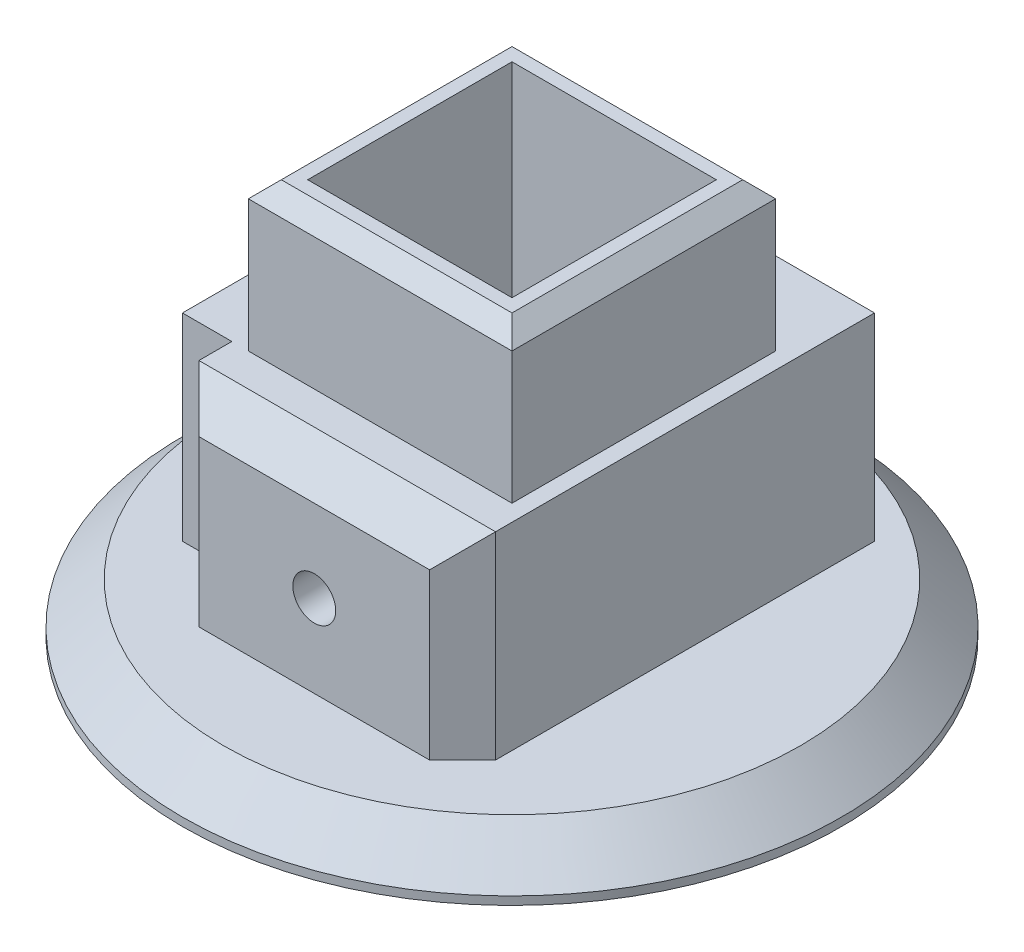
SolidWorks part; units mm, degrees
ref_plane "Front Plane" through (0, 0, 0) normal (0, 0, 1) x (1, 0, 0)
ref_plane "Top Plane" through (0, 0, 0) normal (0, 1, 0) x (1, 0, 0)
ref_plane "Right Plane" through (0, 0, 0) normal (1, 0, 0) x (0, 0, -1)
sketch "Sketch1" plane through (0, 0, 0) normal (0, 1, 0) x (1, 0, 0)
  line L0 (0, 16) -> (0, 0) construction
  line L1 (-8, 16) -> (8, 16)
  line L2 (-8, 16) -> (-8, 0)
  line L10 (8, 16) -> (8, 0)
  line L11 (-8, 0) -> (8, 0)
  dimension "D1" = 16
  dimension "D2" = 16
extrude "Boss-Extrude1" add sketch "Sketch1" along normal blind 24
sketch "Sketch12" plane through (0, 24, 0) normal (0, 1, 0) x (1, 0, 0)
  line L1 (-6.2, 14.2) -> (6.2, 14.2)
  line L2 (-6.2, 14.2) -> (-6.2, 1.8)
  line L3 (-6.2, 1.8) -> (6.2, 1.8)
  line L4 (6.2, 14.2) -> (6.2, 1.8)
  line L5 (0, 0) -> (0, 16) construction
  line L6 (8, 8) -> (-13.65, 8) construction
  line L7 (8, 16) -> (8, 0) construction
  dimension "D1" = 12.4
  dimension "D2" = 12.4
extrude "Cut-Extrude6" cut sketch "Sketch12" against normal offset from surface (22 mm away) 2 up to face at (0, 0, -8)
sketch "Sketch13" plane through (0, 0, 0) normal (0, 1, 0) x (1, 0, 0)
  line L0 (0, 16) -> (0, 0) construction
  circle A0 centre (0, 8) radius 20
  dimension "D1" = 40
extrude "Boss-Extrude2" add sketch "Sketch13" along normal blind 3
chamfer "Chamfer1" distance 2.5 angle 45 1 edges at (0, 3, 12)
sketch "Sketch14" plane through (0, 3, 0) normal (0, 1, 0) x (1, 0, 0)
  line L1 (-8, 16) -> (8, 16)
  line L3 (-8, 23) -> (8, 23)
  line L5 (-8, 0) -> (8, 0)
  line L7 (-8, -4) -> (8, -4)
  line L9 (0, 0) -> (0, 24.5816) construction
  line L10 (-8, 23) -> (-9, 23)
  line L11 (-8, 16) -> (-8, 0)
  line L12 (-8, -4) -> (-9, -4)
  line L13 (-9, 23) -> (-9, -4)
  line L14 (8, -4) -> (9, -4)
  line L15 (8, 23) -> (9, 23)
  line L16 (9, 23) -> (9, -4)
  line L17 (8, 16) -> (8, 0) construction
  line L18 (8, 16) -> (8, 0)
  dimension "D1" = 7
  dimension "D2" = 4
  dimension "D3" = 1
extrude "Boss-Extrude3" add sketch "Sketch14" along normal blind 12
sketch "Sketch5" plane through (0, 0, -23) normal (0, 0, -1) x (-1, 0, 0)
  line L0 (0, 24) -> (0, 0) construction
  line L3 (-22.5, 8) -> (22.5, 8) construction
  line L4 (-2.1, 11.1) -> (2.1, 11.1)
  line L5 (-3.1, 10.1) -> (-3.1, 8.8)
  line L6 (-3.1, 4.9) -> (3.1, 4.9)
  line L7 (3.1, 10.1) -> (3.1, 8.8)
  line L10 (-2.1, 11.1) -> (-3.1, 10.1)
  line L11 (2.1, 11.1) -> (3.1, 10.1)
  line L12 (-3.1, 7.2) -> (-3.1, 4.9)
  line L13 (3.1, 7.2) -> (3.1, 4.9)
  line L14 (-8, 24) -> (8, 24) construction
  arc A0 (-3.1, 8.8) -> (-3.1, 7.2) centre (-3.1, 8) ccw
  arc A1 (3.1, 8.8) -> (3.1, 7.2) centre (3.1, 8) cw
  point P6 (-3.1, 11.1)
  dimension "D4" = 0.8
  dimension "D1" = 8
  dimension "D2" = 6.2
  dimension "D3" = 6.2
extrude "Cut-Extrude1" cut sketch "Sketch5" against normal blind 7.5
sketch "Sketch11" plane through (0, 11.1, 0) normal (0, -1, 0) x (1, 0, 0)
  line L0 (2.1, -15.5) -> (2.1, -23) construction
  line L1 (-2.1, -15.5) -> (2.1, -15.5)
  line L2 (-2.1, -15.5) -> (-2.1, -21)
  line L3 (-2.1, -21) -> (2.1, -21)
  line L4 (2.1, -15.5) -> (2.1, -21)
  line L6 (22.5, -23) -> (-22.5, -23) construction
  dimension "D1" = 2
extrude "Cut-Extrude5" cut sketch "Sketch11" against normal blind 0.1 and the other way blind 6.3
chamfer "Chamfer2" distance 2 angle 45 3 edges at (-9, 9, -23) (9, 9, -23) (0, 15, -23)
chamfer "Chamfer4" distance 2 angle 45 3 edges at (0, 15, 4) (9, 9, 4) (-9, 9, 4)
sketch "Sketch15" plane through (0, 0, -15.5) normal (0, 0, -1) x (-1, 0, 0)
  line L0 (-22.5, 8) -> (22.5, 8) construction
  circle A0 centre (0, 8) radius 1.3
  dimension "D1" = 2.6
extrude "Cut-Extrude7" cut sketch "Sketch15" against normal through all
chamfer "Chamfer5" distance 1 angle 45 4 edges at (0, 24, 0) (-8, 24, -8) (0, 24, -16) (8, 24, -8)
sketch "Esquisse3" plane through (-9, 0, 0) normal (-1, 0, 0) x (0, 0, 1)
  line L0 (9.5, 3) -> (-25.5, 3) construction
  line L1 (0, 3) -> (-15.9265, 3)
  line L2 (0, 3) -> (0, 15)
  line L3 (0, 15) -> (-15.9265, 15)
  line L4 (-15.9265, 3) -> (-15.9265, 15)
  line L5 (-21, 15) -> (2, 15) construction
extrude "Boss.-Extru.1" add sketch "Esquisse3" along normal blind 5
sketch "Esquisse4" plane through (-14, 0, 0) normal (-1, 0, 0) x (0, 0, 1)
  line L0 (-7.965, 24.7266) -> (-7.965, 0.7266) construction
  line L1 (-30.6321, 8) -> (14.3679, 8) construction
  line L2 (-10.065, 11.1) -> (-5.865, 11.1)
  line L3 (-11.065, 10.1) -> (-11.065, 8.8)
  line L4 (-11.065, 4.9) -> (-4.865, 4.9)
  line L5 (-4.865, 10.1) -> (-4.865, 8.8)
  line L6 (-10.065, 11.1) -> (-11.065, 10.1)
  line L7 (-5.865, 11.1) -> (-4.865, 10.1)
  line L8 (-11.065, 7.2) -> (-11.065, 4.9)
  line L9 (-4.865, 7.2) -> (-4.865, 4.9)
  line L10 (-15.9265, 3) -> (0, 3) construction
  line L11 (0, 3) -> (0, 15) construction
  line L13 (-15.9265, 15) -> (-15.9265, 3) construction
  arc A0 (-11.065, 8.8) -> (-11.065, 7.2) centre (-11.065, 8) ccw
  arc A1 (-4.865, 8.8) -> (-4.865, 7.2) centre (-4.865, 8) cw
  point P2 (-11.065, 11.1)
  dimension "D1" = 1.9
  dimension "D2" = 4.865
  dimension "D3" = 6.2
  dimension "D4" = 4.8615
extrude "Enlèv. mat.-Extru.1" cut sketch "Esquisse4" against normal blind 7
sketch "Esquisse5" plane through (-7, 0, 0) normal (-1, 0, 0) x (0, 0, 1)
  line L0 (-11.065, 4.9) -> (-4.865, 4.9) construction
  line L3 (-11.065, 10.1) -> (-11.065, 8.8) construction
  circle A0 centre (-7.965, 8) radius 1.3
  point P2 (0, 0)
  point P7 (-11.065, 8.8)
  dimension "D1" = 2.6
  dimension "D2" = 3.1
  dimension "D3" = 3.1
extrude "Enlèv. mat.-Extru.2" cut sketch "Esquisse5" against normal blind 5
chamfer "Chanfrein2" distance 2 angle 45 1 edges at (-14, 15, -7.9633)
chamfer "Chanfrein3" distance 2 angle 45 1 edges at (-14, 8, 0)
chamfer "Chanfrein4" distance 2 angle 45 1 edges at (-14, 8, -15.9265)
